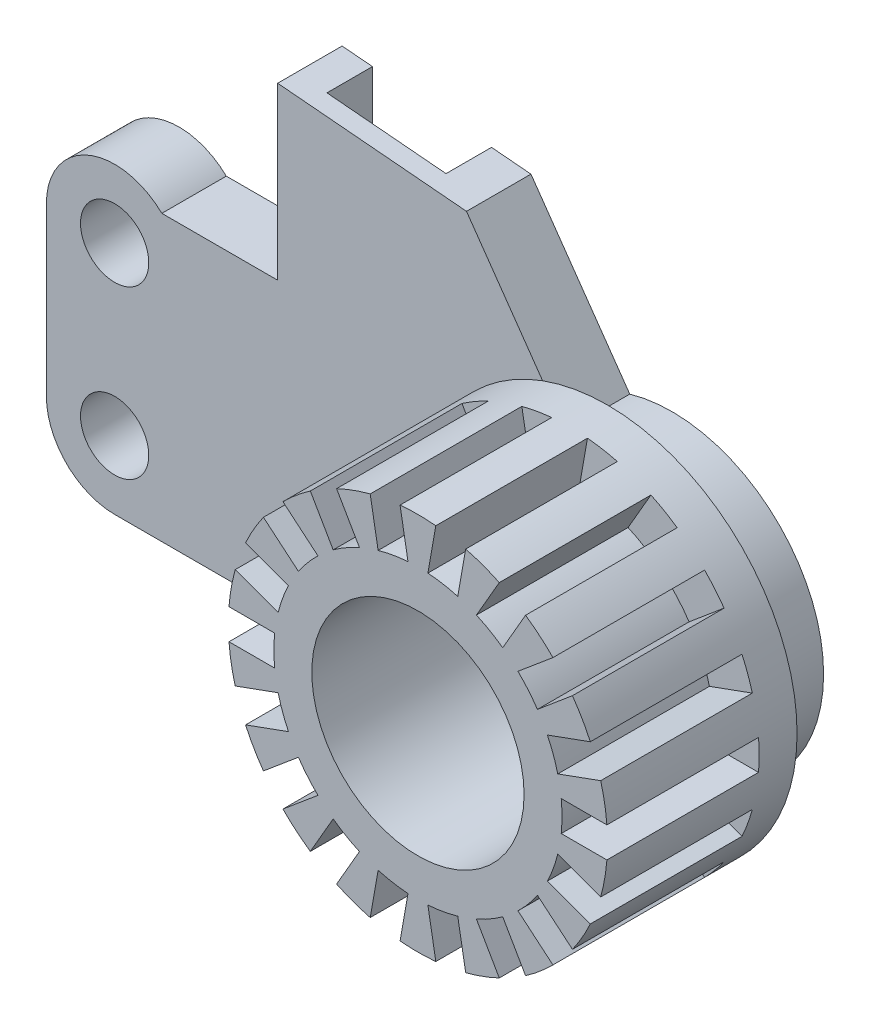
SolidWorks part; units mm, degrees
ref_plane "Front Plane" through (0, 0, 0) normal (0, 0, 1) x (1, 0, 0)
ref_plane "Top Plane" through (0, 0, 0) normal (0, 1, 0) x (1, 0, 0)
ref_plane "Right Plane" through (0, 0, 0) normal (1, 0, 0) x (0, 0, -1)
sketch "Sketch1" plane through (0, 0, 0) normal (0, 1, 0) x (1, 0, 0)
  line L0 (-25, 0) -> (-14, 0)
  line L1 (-14, 0) -> (-14, 28.5)
  line L2 (-14, 28.5) -> (-15.5, 28.5)
  line L3 (-15.5, 28.5) -> (-15.5, 33.5)
  line L4 (-15.5, 33.5) -> (-20, 33.5)
  line L5 (-20, 33.5) -> (-20, 25)
  line L6 (-20, 25) -> (-25, 25)
  line L7 (-25, 25) -> (-25, 0)
  line L8 (0, 0) -> (0, 31.2664) construction
  dimension "D1" = 14
  dimension "D2" = 25
  dimension "D3" = 33.5
  dimension "D4" = 8.5
  dimension "D5" = 5
  dimension "D6" = 15.5
  dimension "D7" = 20
revolve "Revolve2" add sketch "Sketch1" angle 360 about L8
sketch "Sketch2" plane through (0, 0, 0) normal (0, 0, 1) x (1, 0, 0)
  line L1 (18.8944, 2) -> (24.9199, 2)
  line L2 (18.8944, -2) -> (24.9199, -2)
  line L3 (19, 0) -> (33.8306, 0) construction
  circle A0 centre (0, 0) radius 25 construction
  arc A2 (24.9199, -2) -> (24.9199, 2) centre (0, 0) ccw
  arc A4 (18.8944, -2) -> (18.8944, 2) centre (0, 0) ccw
  point P3 (18.9893, -2.6389)
  dimension "D2" = 38
  dimension "D1" = 4
extrude "Cut-Extrude1" cut sketch "Sketch2" against normal blind 20
pattern_circular "CirPattern1" count 18 over 360 about axis through (0, 0, 0) along (0, 0, 1) of "Cut-Extrude1"
sketch "Sketch3" plane through (0, 0, -33.5) normal (0, 0, -1) x (-1, 0, 0)
  line L0 (0, 0) -> (85.8537, 0) construction
  line L1 (0, -20) -> (65, -20)
  line L2 (0, 0) -> (0, 62.0879) construction
  line L3 (5.5639, 19.2105) -> (18.5951, 37.8211)
  line L4 (18.5951, 37.8211) -> (43.5, 40)
  line L5 (43.5, 40) -> (43.5, 17.5)
  line L6 (43.5, 17.5) -> (58.7751, 17.5)
  line L7 (43.5, 40) -> (6.2365, 40) construction
  line L8 (74, 11) -> (74, -11)
  circle A0 centre (0, 0) radius 20 construction
  arc A1 (0, -20) -> (5.5639, 19.2105) centre (0, 0) ccw
  arc A4 (65, -20) -> (74, -11) centre (65, -11) ccw
  arc A5 (58.7751, 17.5) -> (74, 11) centre (65, 11) cw
  circle A6 centre (65, 11) radius 4.5
  circle A8 centre (65, -11) radius 4.5
  dimension "D1" = 18
  dimension "D8" = 9
  dimension "D2" = 65
  dimension "D3" = 37.5
  dimension "D4" = 5
  dimension "D5" = 35
  dimension "D6" = 43.5
  dimension "D7" = 25
  dimension "D9" = 40
extrude "Boss-Extrude1" add sketch "Sketch3" against normal blind 8.5
sketch "Sketch6" plane through (0, 0, -33.5) normal (0, 0, -1) x (-1, 0, 0)
  line L0 (0, 0) -> (18.0156, 8.6855) construction
  line L1 (0, 0) -> (44.1258, 16.0605) construction
  line L2 (74, -11) -> (74, 11) construction
  line L7 (0, -16) -> (65, -16)
  line L8 (20.7846, -16) -> (52.0385, -16)
  line L10 (21.8717, 35.5268) -> (8.8405, 16.9162)
  line L11 (23.7969, 38.2762) -> (11.7215, 21.0308)
  line L12 (43.5, 40) -> (18.5951, 37.8211) construction
  line L13 (39.5, 17.5) -> (39.5, 40)
  line L14 (39.5, 19.306) -> (39.5, 39.65)
  line L15 (0, 0) -> (36.6387, 0) construction
  line L16 (39.5, 39.65) -> (23.7969, 38.2762)
  line L19 (58.7751, 13.5) -> (43.5, 13.5)
  line L20 (52.0868, 13.5) -> (42.9386, 13.5)
  line L21 (65, 2) -> (70, 2)
  line L22 (21.1524, 9.8272) -> (36.8681, 15.5472)
  line L23 (22.5205, 6.0684) -> (42.9386, 13.5)
  line L24 (65, -2) -> (70, -2)
  line L25 (70, -2) -> (70, 2)
  arc A0 (16.487, 11.3217) -> (12.4984, 15.6137) centre (0, 0) ccw
  arc A1 (56.0601, 9.9615) -> (65, 2) centre (65, 11) ccw
  arc A2 (74, 11) -> (58.7751, 17.5) centre (65, 11) ccw construction
  arc A3 (65, -2) -> (56.0267, -11.6923) centre (65, -11) ccw
  arc A4 (65, -20) -> (74, -11) centre (65, -11) ccw construction
  arc A5 (17.3205, -10) -> (19.9072, 1.9247) centre (0, 0) ccw
  arc A6 (5.5639, 19.2105) -> (0, -20) centre (0, 0) ccw construction
  arc A7 (22.5205, 6.0684) -> (19.9072, 1.9247) centre (23.8886, 2.3097) ccw
  arc A8 (17.3205, -10) -> (20.7846, -16) centre (20.7846, -12) ccw
  arc A9 (56.0267, -11.6923) -> (52.0385, -16) centre (52.0385, -12) cw
  arc A10 (56.0601, 9.9615) -> (52.0868, 13.5) centre (52.0868, 9.5) ccw
  arc A11 (36.8681, 15.5472) -> (39.5, 19.306) centre (35.5, 19.306) ccw
  arc A12 (12.4984, 15.6137) -> (11.7215, 21.0308) centre (14.9981, 18.7365) cw
  arc A13 (21.1524, 9.8272) -> (16.487, 11.3217) centre (19.7844, 13.586) cw
  point P42 (0, -0.3547)
  dimension "D5" = 20
  dimension "D7" = 4
  dimension "D9" = 4
  dimension "D4" = 4
  dimension "D8" = 4
  dimension "D1" = 4
  dimension "D2" = 4
  dimension "D3" = 4
  dimension "D6" = 4
extrude "Cut-Extrude2" cut sketch "Sketch6" against normal blind 6
